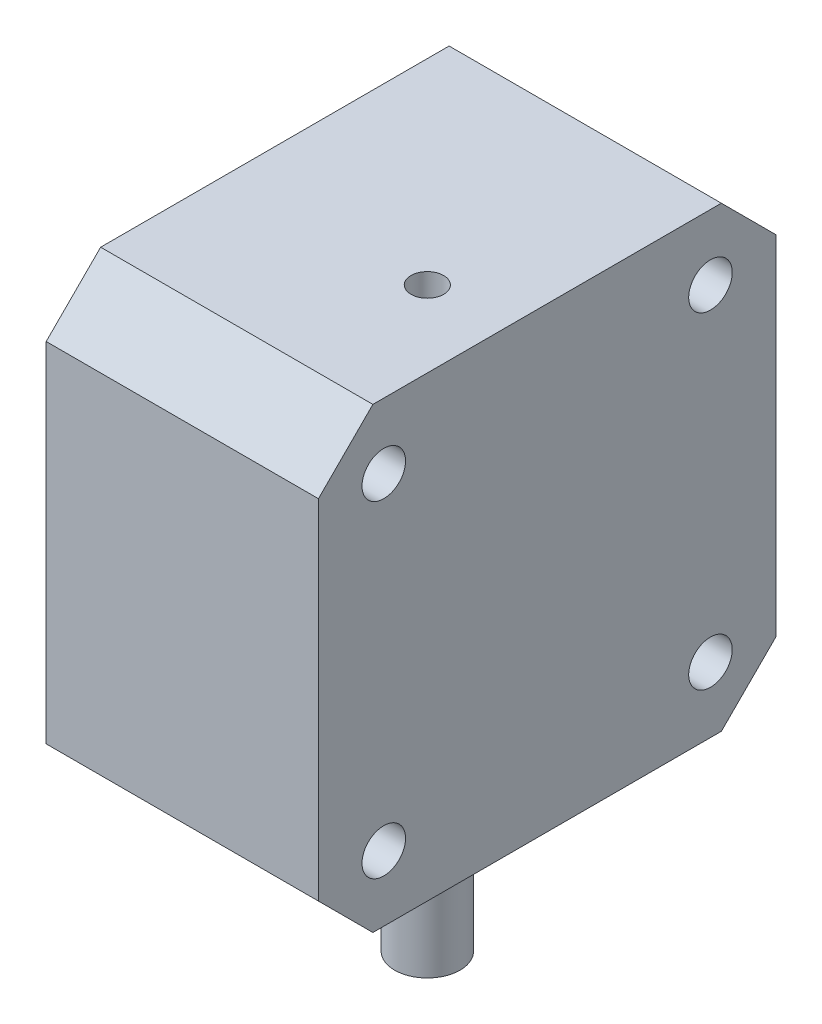
SolidWorks part; units mm, degrees
ref_plane "Front Plane" through (0, 0, 0) normal (0, 0, 1) x (1, 0, 0)
ref_plane "Top Plane" through (0, 0, 0) normal (0, 1, 0) x (1, 0, 0)
ref_plane "Right Plane" through (0, 0, 0) normal (1, 0, 0) x (0, 0, -1)
sketch "Sketch1" plane through (0, 0, 0) normal (1, 0, 0) x (0, 0, -1)
  line L1 (0, 0) -> (42, 0)
  line L2 (0, 0) -> (0, 42)
  line L3 (0, 42) -> (42, 42)
  line L4 (42, 0) -> (42, 42)
  dimension "D1" = 42
extrude "Boss-Extrude1" add sketch "Sketch1" along normal blind 25
sketch "Sketch2" plane through (0, 0, 0) normal (0, -1, 0) x (1, 0, 0)
  circle A0 centre (18, -17) radius 3
  dimension "D3" = 6
  dimension "D1" = 17
  dimension "D2" = 18
extrude "Boss-Extrude2" add sketch "Sketch2" along normal blind 11
sketch "Sketch3" plane through (25, 0, 0) normal (1, 0, 0) x (0, 0, -1)
  line L0 (42, 0) -> (42, 42) construction
  line L1 (6, 6) -> (36, 6)
  line L2 (6, 6) -> (6, 36)
  line L3 (6, 36) -> (36, 36)
  line L4 (36, 6) -> (36, 36)
  line L5 (6, 6) -> (36, 36) construction
  line L6 (6, 36) -> (36, 6) construction
  line L7 (0, 0) -> (42, 0) construction
  circle A0 centre (6, 6) radius 2
  circle A1 centre (36, 6) radius 2
  circle A2 centre (36, 36) radius 2
  circle A3 centre (6, 36) radius 2
  point P0 (21, 21)
  point P11 (42, 21)
  point P14 (21, 0)
  dimension "D1" = 4
  dimension "D2" = 30
extrude "Cut-Extrude1" cut sketch "Sketch3" against normal blind 42 contours L3 A3 L2 | L2 A3 L3 | L3 A2 L4 | L4 A2 L3 | L1 A0 L2 | L2 A0 L1 | L4 A1 L1 | L1 A1 L4
sketch "Sketch4" plane through (0, -11, 0) normal (0, -1, 0) x (1, 0, 0)
  circle A0 centre (18, -17) radius 1.5
  dimension "D1" = 3
extrude "Cut-Extrude2" cut sketch "Sketch4" against normal blind 100
chamfer "Chamfer2" distance 5 angle 45 4 edges at (12.5, 0, 0) (12.5, 0, -42) (12.5, 42, 0) (12.5, 42, -42)
